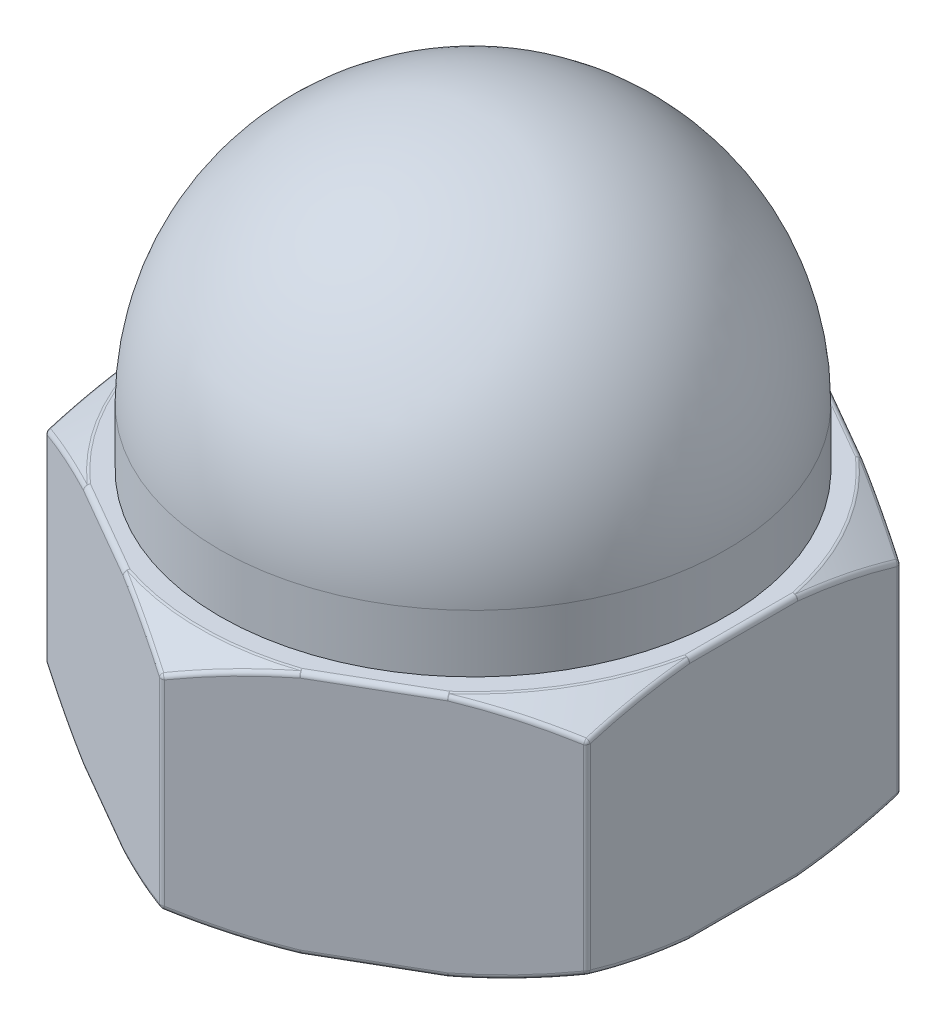
SolidWorks part; units mm, degrees
ref_plane "Alzado" through (0, 0, 0) normal (0, 0, 1) x (1, 0, 0)
ref_plane "Planta" through (0, 0, 0) normal (0, 1, 0) x (1, 0, 0)
ref_plane "Vista lateral" through (0, 0, 0) normal (1, 0, 0) x (0, 0, -1)
sketch "Croquis1" plane through (0, 0, 0) normal (0, 1, 0) x (1, 0, 0)
  line L0 (-2.7, 1.5588) -> (0, 3.1177)
  line L1 (0, 3.1177) -> (2.7, 1.5588)
  line L2 (2.7, 1.5588) -> (2.7, -1.5588)
  line L3 (2.7, -1.5588) -> (0, -3.1177)
  line L4 (0, -3.1177) -> (-2.7, -1.5588)
  line L5 (-2.7, -1.5588) -> (-2.7, 1.5588)
  circle A0 centre (0, 0) radius 3.1177 construction
  dimension "D1" = 5.4
extrude "Saliente-Extruir1" add sketch "Croquis1" along normal blind 2.45 contours L5 L4 L3 L2 L1 L0
ref_plane "Plano1" through (0, 0, 0) normal (0.5, 0, 0.866) x (0.866, 0, -0.5)
ref_plane "Plano2" through (0, 1.225, 0) normal (0, 1, 0) x (1, 0, 0)
sketch "Croquis3" plane through (0, 0, 0) normal (0.5, 0, 0.866) x (0.866, 0, -0.5)
  line L2 (-1.5588, 0) -> (-3.1177, 0) construction
  line L3 (-3.1177, 2.2264) -> (-3.1177, 4.2264) construction
  line L4 (-3.1177, 4.2264) -> (0, 4.2264) construction
  line L5 (3.1177, 4.2264) -> (3.1177, 2.2264)
  line L6 (0, 0) -> (0, 3.1) construction
  line L7 (0, 3.1) -> (0, 4.2264)
  line L8 (3.1177, 4.2264) -> (0, 4.2264)
  line L12 (3.1177, 2.45) -> (3.1177, 0) construction
  line L13 (-3.1177, 2.45) -> (-3.1177, 0) construction
  arc A0 (3.1177, 2.2264) -> (0, 3.1) centre (0, -2.9) ccw
  arc A1 (0, 3.1) -> (-3.1177, 2.2264) centre (0, -2.9) ccw construction
  dimension "D2" = 2
  dimension "D3" = 6
  dimension "D1" = 2.9
revolve "Cortar-Revolución4" cut sketch "Croquis3" angle 360 about L6
mirror "Simetría1" about plane through (0, 1.225, 0) normal (0, 1, 0) of "Cortar-Revolución4"
sketch "Croquis2" plane through (0, 2.45, 0) normal (0, 1, 0) x (1, 0, 0)
  circle A0 centre (0, 0) radius 2.525
  dimension "D1" = 5.05
extrude "Saliente-Extruir2" add sketch "Croquis2" along normal blind 3.1
fillet "Redondeo1" radius 2.525 1 edges at (0, 5.55, 2.525)
fillet "Redondeo2" radius 0.05 53 edges at (-2.7, 0, 0) (-2.7, 0.0739, -0.934) (-2.7, 2.3761, -0.934) (-2.7, 2.45, 0) (-2.7, 2.3761, 0.934) (-2.7, 0.0739, 0.934) (-1.35, 0, -2.3383) (-0.5411, 0.0739, -2.8053) (-0.5411, 2.3761, -2.8053) (-1.35, 2.45, -2.3383) (-2.1589, 2.3761, -1.8712) (-2.7, 1.225, -1.5588) (-2.1589, 0.0739, -1.8712) (1.35, 0, -2.3383) (2.1589, 0.0739, -1.8712) (2.1589, 2.3761, -1.8712) (1.35, 2.45, -2.3383) (0.5411, 2.3761, -2.8053) (0, 1.225, -3.1177) (0.5411, 0.0739, -2.8053) (2.7, 0, 0) (2.7, 0.0739, 0.934) (2.7, 2.3761, 0.934) (2.7, 2.45, 0) (2.7, 2.3761, -0.934) (2.7, 1.225, -1.5588) (2.7, 0.0739, -0.934) (-1.35, 0, 2.3383) (-2.1589, 0.0739, 1.8712) (-2.7, 1.225, 1.5588) (-2.1589, 2.3761, 1.8712) (-1.35, 2.45, 2.3383) (-0.5411, 2.3761, 2.8053) (-0.5411, 0.0739, 2.8053) (1.35, 0, 2.3383) (0.5411, 0.0739, 2.8053) (0, 1.225, 3.1177) (0.5411, 2.3761, 2.8053) (1.35, 2.45, 2.3383) (2.1589, 2.3761, 1.8712) (2.7, 1.225, 1.5588) (2.1589, 0.0739, 1.8712) (-2.3523, 0, 1.3581) (0, 0, 2.7162) (2.3523, 0, 1.3581) (2.3523, 0, -1.3581) (0, 0, -2.7162) (-2.3523, 0, -1.3581) (-2.3523, 2.45, 1.3581) (0, 2.45, 2.7162) (2.3523, 2.45, 1.3581) (2.3523, 2.45, -1.3581) (0, 2.45, -2.7162)
sketch "Croquis4" plane through (0, 0, 0) normal (0, -1, 0) x (1, 0, 0)
  circle A0 centre (0, 0) radius 1.15
  dimension "D1" = 2.3
extrude "Cortar-Extruir1" cut sketch "Croquis4" against normal blind 4.85
chamfer "Chaflán1" distance 0.2 angle 45 1 edges at (0, 0, -1.15)
